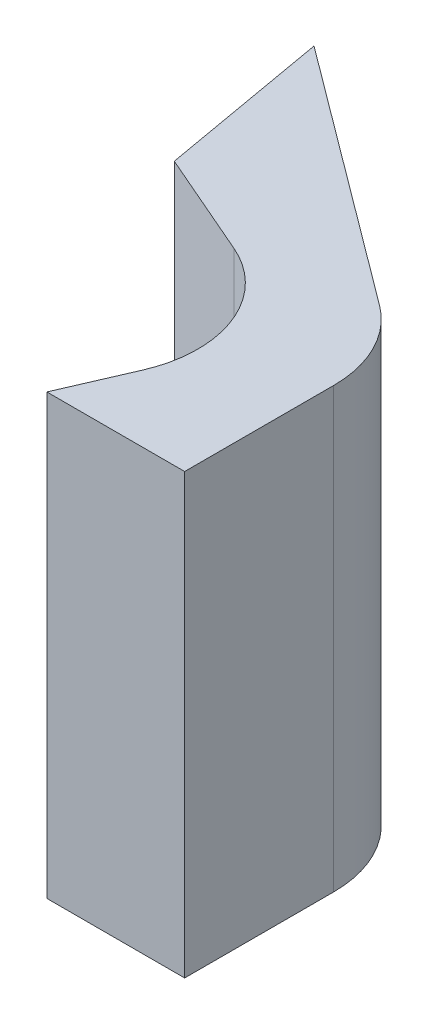
SolidWorks part; units mm, degrees
material "ABS"
ref_plane "前视基准面" through (0, 0, 0) normal (0, 0, 1) x (1, 0, 0)
ref_plane "上视基准面" through (0, 0, 0) normal (0, 1, 0) x (1, 0, 0)
ref_plane "右视基准面" through (0, 0, 0) normal (1, 0, 0) x (0, 0, -1)
sketch "草图1" plane through (0, 0, 0) normal (0, 1, 0) x (1, 0, 0)
  line L0 (0, 0) -> (12, 0)
  line L1 (12, 0) -> (12, 12.9818)
  line L2 (7.9767, 20.9992) -> (-14.4575, 37.7231)
  line L3 (-14.4575, 37.7231) -> (-11.8528, 22.9509)
  line L4 (-11.8528, 22.9509) -> (-2.677, 18.9755)
  line L5 (2.5234, 5.8242) -> (0, 0)
  arc A0 (7.9767, 20.9992) -> (12, 12.9818) centre (2, 12.9818) cw
  arc A1 (2.5234, 5.8242) -> (-2.677, 18.9755) centre (-6.6525, 9.7997) ccw
  point P3 (0, 0)
  point P8 (-14.4504, 39.6861)
  point P9 (12, 18.2308)
  point P12 (12, 18)
  point P15 (6.4988, 15)
  dimension "D9" = 10
  dimension "D1" = 12
  dimension "D2" = 100
  dimension "D3" = 15
  dimension "D4" = 90
  dimension "D5" = 18
  dimension "D6" = 15
  dimension "D7" = 33
  dimension "D8" = 20
extrude "凸台-拉伸1" add sketch "草图1" along normal blind 38.2
